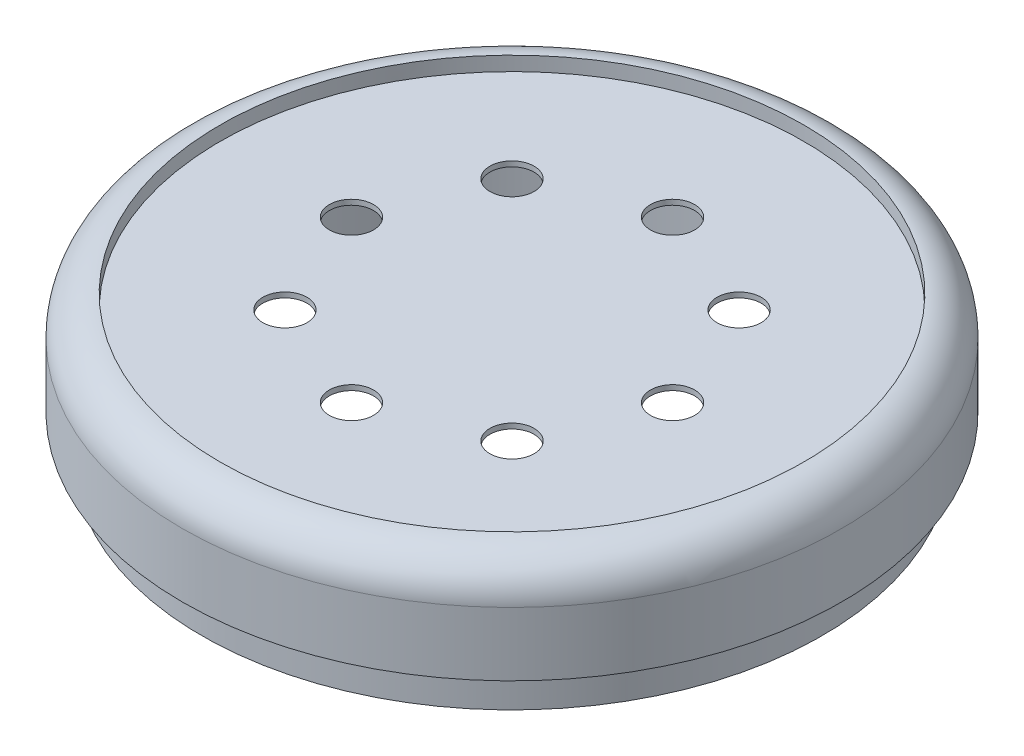
SolidWorks part; units mm, degrees
ref_plane "Front Plane" through (0, 0, 0) normal (0, 0, 1) x (1, 0, 0)
ref_plane "Top Plane" through (0, 0, 0) normal (0, 1, 0) x (1, 0, 0)
ref_plane "Right Plane" through (0, 0, 0) normal (1, 0, 0) x (0, 0, -1)
sketch "Sketch1" plane through (0, 0, 0) normal (0, 1, 0) x (1, 0, 0)
  circle A0 centre (0, 0) radius 25.4
  dimension "D1" = 50.8
extrude "Boss-Extrude1" add sketch "Sketch1" along normal blind 10.9
sketch "Sketch4" plane through (0, 0, 0) normal (0, -1, 0) x (1, 0, 0)
  circle A0 centre (0, 0) radius 23.9
  dimension "D1" = 47.8
extrude "Cut-Extrude3" cut sketch "Sketch4" against normal blind 3 flip side to cut
shell "Shell2" thickness 1.5
sketch "Sketch2" plane through (0, 10.9, 0) normal (0, 1, 0) x (1, 0, 0)
  circle A0 centre (0, 12.3756) radius 1.7
  circle A1 centre (8.7509, 8.7509) radius 1.7
  circle A2 centre (12.3756, 0) radius 1.7
  circle A3 centre (8.7509, -8.7509) radius 1.7
  circle A4 centre (0, -12.3756) radius 1.7
  circle A5 centre (-8.7509, -8.7509) radius 1.7
  circle A6 centre (-12.3756, 0) radius 1.7
  circle A7 centre (-8.7509, 8.7509) radius 1.7
  point P18 (0, 0)
  dimension "D1" = 3.4
  dimension "D2" = 8
extrude "Cut-Extrude1" cut sketch "Sketch2" against normal through all
fillet "Fillet1" radius 3 1 edges at (0, 10.9, 25.4)
sketch "Sketch3" plane through (0, 10.9, 0) normal (0, 1, 0) x (1, 0, 0)
  circle A0 centre (0, 0) radius 22.5
  dimension "D1" = 45
extrude "Cut-Extrude2" cut sketch "Sketch3" against normal blind 1.1
